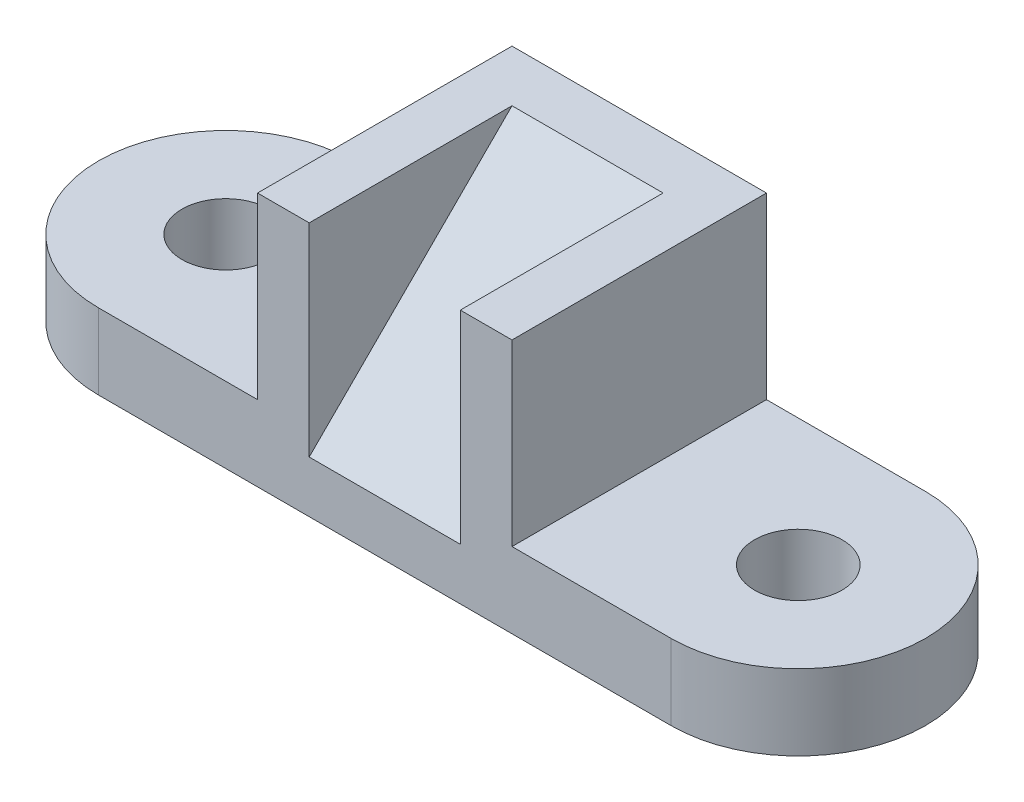
SolidWorks part; units mm, degrees
ref_plane "Front Plane" through (0, 0, 0) normal (0, 0, 1) x (1, 0, 0)
ref_plane "Top Plane" through (0, 0, 0) normal (0, 1, 0) x (1, 0, 0)
ref_plane "Right Plane" through (0, 0, 0) normal (1, 0, 0) x (0, 0, -1)
sketch "Sketch1" plane through (0, 0, 0) normal (0, 1, 0) x (1, 0, 0)
  line L0 (-72, 0) -> (72, 0) construction
  line L1 (-72, 32) -> (72, 32)
  line L2 (-72, -32) -> (72, -32)
  arc A0 (-72, 32) -> (-72, -32) centre (-72, 0) ccw
  arc A1 (72, -32) -> (72, 32) centre (72, 0) ccw
  circle A2 centre (-72, 0) radius 11
  circle A3 centre (72, 0) radius 11
  point P2 (0, 0)
  dimension "D2" = 22
  dimension "D3" = 22
  dimension "D4" = 32
  dimension "D1" = 144
extrude "Boss-Extrude1" add sketch "Sketch1" along normal blind 19
sketch "Sketch2" plane through (0, 19, 0) normal (0, 1, 0) x (1, 0, 0)
  line L0 (-72, -32) -> (72, -32) construction
  line L1 (-32, 32) -> (32, 32)
  line L2 (-32, 32) -> (-32, -32)
  line L3 (-32, -32) -> (32, -32)
  line L4 (32, 32) -> (32, -32)
  line L5 (-32, 32) -> (32, -32) construction
  line L6 (-32, -32) -> (32, 32) construction
  point P0 (0, 0)
  dimension "D1" = 64
  dimension "D2" = 64
extrude "Boss-Extrude2" add sketch "Sketch2" along normal blind 45
sketch "Sketch4" plane through (-32, 0, 0) normal (-1, 0, 0) x (0, 0, 1)
  line L0 (32, 64) -> (-19, 64)
  line L1 (-32, 64) -> (32, 64) construction
  line L2 (-19, 64) -> (32, 13)
  line L3 (32, 19) -> (32, 0) construction
  line L4 (32, 13) -> (32, 64)
  dimension "D1" = 13
  dimension "D2" = 13
extrude "Cut-Extrude2" cut sketch "Sketch4" against normal blind 38 from offset 13 contours L4 L0 L2
